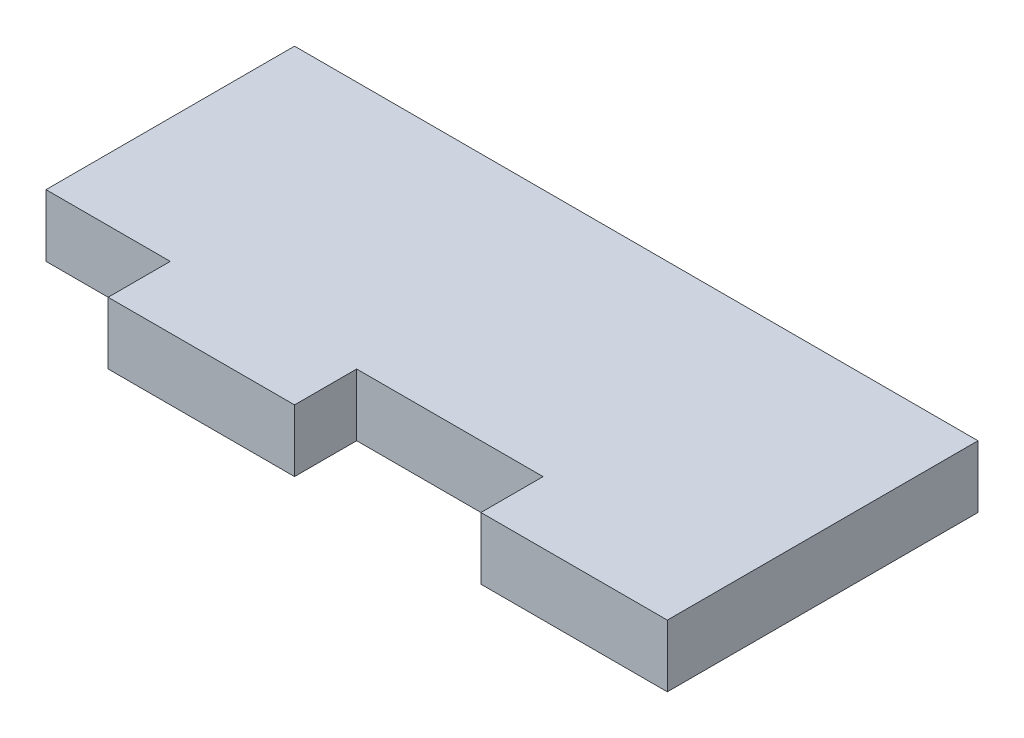
SolidWorks part; units mm, degrees
material "Maple"
ref_plane "Front Plane" through (0, 0, 0) normal (0, 0, 1) x (1, 0, 0)
ref_plane "Top Plane" through (0, 0, 0) normal (0, 1, 0) x (1, 0, 0)
ref_plane "Right Plane" through (0, 0, 0) normal (1, 0, 0) x (0, 0, -1)
sketch "Sketch1" plane through (0, 0, 0) normal (0, 1, 0) x (1, 0, 0)
  line L0 (-69.85, 25.4) -> (0, 25.4)
  line L1 (0, 0) -> (-69.85, 0) construction
  line L2 (0, 0) -> (0, 25.4) construction
  line L3 (0, 25.4) -> (-69.85, 25.4) construction
  line L4 (-69.85, 0) -> (-69.85, 25.4) construction
  line L5 (0, 0) -> (-19.05, 0) construction
  line L6 (0, 0) -> (0, -6.35) construction
  line L7 (0, -6.35) -> (-19.05, -6.35) construction
  line L8 (-19.05, 0) -> (-19.05, -6.35) construction
  line L9 (-57.15, 0) -> (-38.1, 0) construction
  line L10 (-57.15, 0) -> (-57.15, -6.35) construction
  line L11 (-57.15, -6.35) -> (-38.1, -6.35) construction
  line L12 (-38.1, 0) -> (-38.1, -6.35) construction
  line L13 (0, 25.4) -> (0, -6.35)
  line L14 (0, -6.35) -> (-19.05, -6.35)
  line L15 (-19.05, -6.35) -> (-19.05, 0)
  line L16 (-19.05, 0) -> (-38.1, 0)
  line L17 (-38.1, 0) -> (-38.1, -6.35)
  line L18 (-38.1, -6.35) -> (-57.15, -6.35)
  line L19 (-57.15, -6.35) -> (-57.15, 0)
  line L20 (-57.15, 0) -> (-69.85, 0)
  line L21 (-69.85, 0) -> (-69.85, 25.4)
  point P12 (0, 0)
  dimension "D1" = 25.4
  dimension "D2" = 6.35
  dimension "D3" = 19.05
  dimension "D4" = 6.35
  dimension "D5" = 19.05
  dimension "D6" = 19.05
  dimension "D7" = 69.85
extrude "Boss-Extrude1" add sketch "Sketch1" along normal blind 6.35
